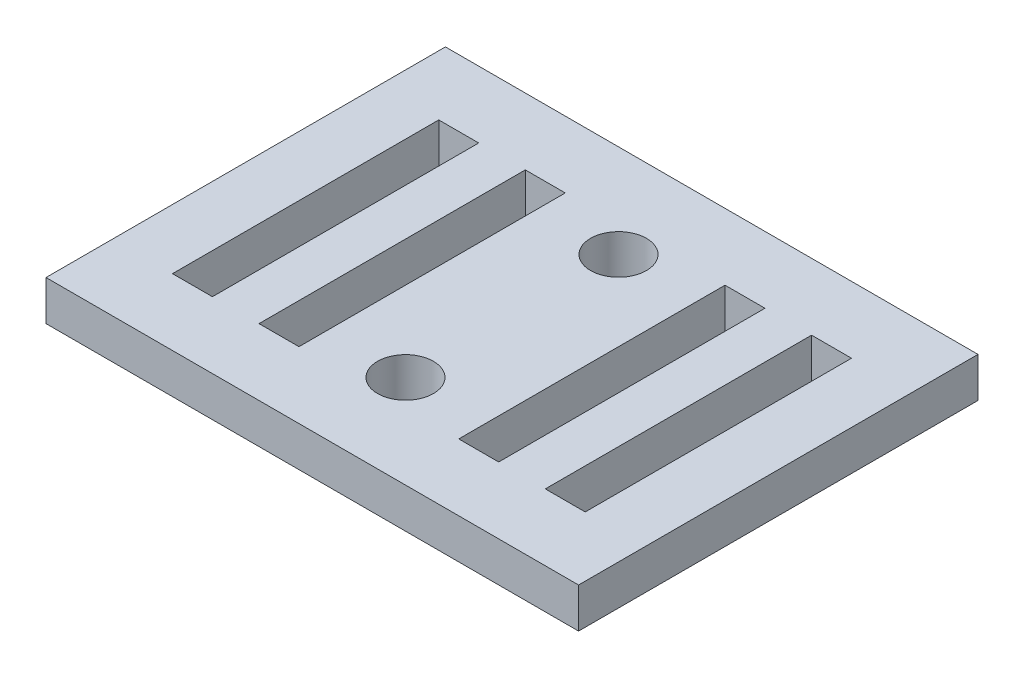
SolidWorks part; units mm, degrees
ref_plane "前视基准面" through (0, 0, 0) normal (0, 0, 1) x (1, 0, 0)
ref_plane "上视基准面" through (0, 0, 0) normal (0, 1, 0) x (1, 0, 0)
ref_plane "右视基准面" through (0, 0, 0) normal (1, 0, 0) x (0, 0, -1)
other "Configuration Table"
sketch "草图1" plane through (0, 0, 0) normal (0, 1, 0) x (1, 0, 0)
  line L0 (20, 0) -> (20, -30)
  line L1 (0, 0) -> (40, 0)
  line L2 (0, 0) -> (0, -30)
  line L3 (0, -30) -> (40, -30)
  line L4 (40, 0) -> (40, -30)
  line L5 (4.5, -5) -> (7.5, -5)
  line L6 (4.5, -5) -> (4.5, -25)
  line L7 (4.5, -25) -> (7.5, -25)
  line L8 (7.5, -5) -> (7.5, -25)
  line L9 (35.5, -25) -> (32.5, -25)
  line L10 (32.5, -5) -> (32.5, -25)
  line L11 (35.5, -5) -> (32.5, -5)
  line L12 (35.5, -5) -> (35.5, -25)
  line L13 (7.5, -15) -> (32.5, -15)
  line L14 (29, -25) -> (26, -25)
  line L15 (11, -5) -> (14, -5)
  line L16 (11, -5) -> (11, -25)
  line L17 (11, -25) -> (14, -25)
  line L18 (14, -5) -> (14, -25)
  line L19 (26, -5) -> (26, -25)
  line L20 (29, -5) -> (26, -5)
  line L21 (29, -5) -> (29, -25)
  circle A0 centre (20, -23) radius 2.1
  circle A1 centre (20, -7) radius 2.1
  dimension "D7" = 4.2
  dimension "D8" = 8
  dimension "D1" = 40
  dimension "D2" = 30
  dimension "D3" = 20
  dimension "D4" = 3
  dimension "D5" = 5
  dimension "D6" = 4.5
  dimension "D9" = 3
  dimension "D10" = 3.5
extrude "凸台-拉伸1" add sketch "草图1" along normal blind 3
